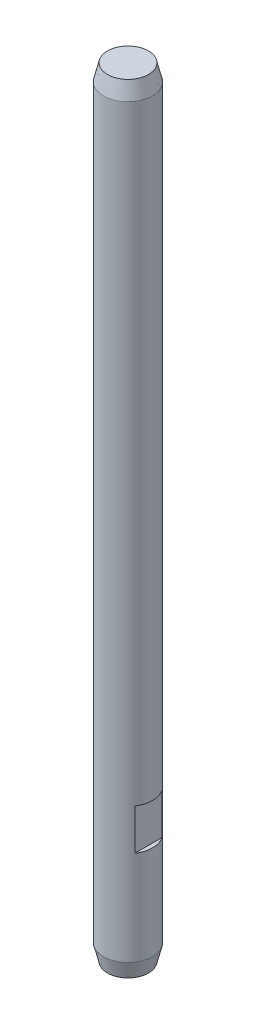
SolidWorks part; units mm, degrees
material "6061-T6 (SS)"
ref_plane "Front Plane" through (0, 0, 0) normal (0, 0, 1) x (1, 0, 0)
ref_plane "Top Plane" through (0, 0, 0) normal (0, 1, 0) x (1, 0, 0)
ref_plane "Right Plane" through (0, 0, 0) normal (1, 0, 0) x (0, 0, -1)
sketch "Sketch1" plane through (0, 0, 0) normal (0, 1, 0) x (1, 0, 0)
  circle A0 centre (0, 0) radius 3
extrude "Boss-Extrude1" add sketch "Sketch1" along normal blind 95
chamfer "Chamfer1" distance 0.5 distance2 2 1 edges at (0, 0, 3)
chamfer "Chamfer2" distance 2 distance2 0.5 1 edges at (0, 95, 3)
ref_plane "Plane1" through (3, 0, 0) normal (1, 0, 0) x (0, 0, -1)
sketch "Sketch2" plane through (3, 0, 0) normal (1, 0, 0) x (0, 0, -1)
  line L0 (0, 3.3) -> (0, -3.3) construction
  line L1 (-3, 18.5) -> (3, 18.5)
  line L2 (-3, 18.5) -> (-3, 13.5)
  line L3 (-3, 13.5) -> (3, 13.5)
  line L4 (3, 18.5) -> (3, 13.5)
  line L5 (-3, 18.5) -> (3, 13.5) construction
  line L6 (-3, 13.5) -> (3, 18.5) construction
  line L7 (55, 0) -> (-55, 0) construction
  point P0 (0, 16)
  dimension "D1" = 13.5
  dimension "D2" = 5
  dimension "D3" = 6
extrude "Cut-Extrude1" cut sketch "Sketch2" against normal blind 0.5
